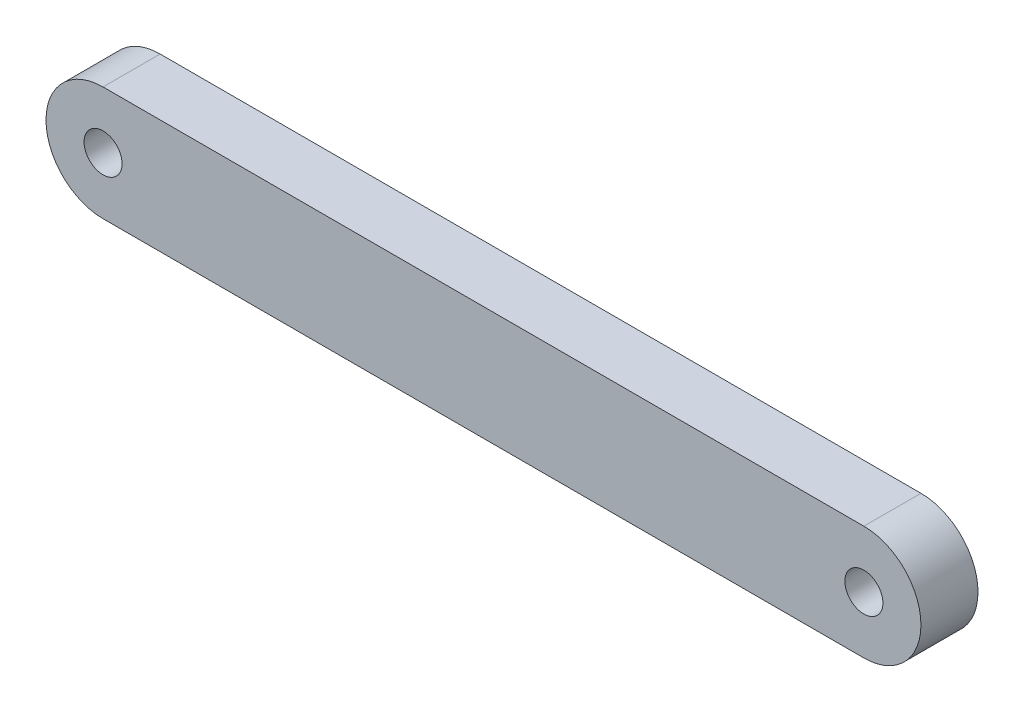
SolidWorks part; units mm, degrees
ref_plane "Front Plane" through (0, 0, 0) normal (0, 0, 1) x (1, 0, 0)
ref_plane "Top Plane" through (0, 0, 0) normal (0, 1, 0) x (1, 0, 0)
ref_plane "Right Plane" through (0, 0, 0) normal (1, 0, 0) x (0, 0, -1)
sketch "Sketch1" plane through (0, 0, 0) normal (0, 0, 1) x (1, 0, 0)
  line L0 (20, 0) -> (-20, 0) construction
  line L1 (20, -3) -> (-20, -3)
  line L2 (20, 3) -> (-20, 3)
  arc A0 (20, -3) -> (20, 3) centre (20, 0) ccw
  arc A1 (-20, 3) -> (-20, -3) centre (-20, 0) ccw
  circle A2 centre (-20, 0) radius 1
  circle A3 centre (20, 0) radius 1
  point P2 (0, 0)
  dimension "D2" = 3
  dimension "D3" = 2
  dimension "D4" = 2
  dimension "D1" = 40
extrude "Boss-Extrude1" add sketch "Sketch1" along normal blind 3
